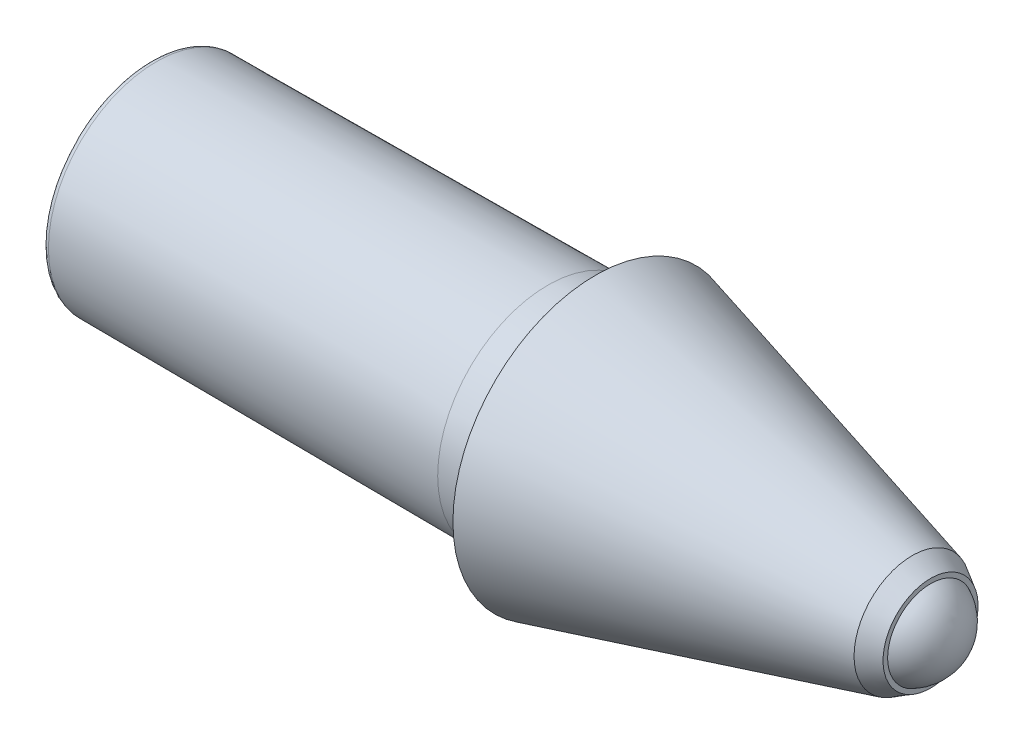
SolidWorks part; units mm, degrees
material "Latão"
ref_plane "Frontal" through (0, 0, 0) normal (0, 0, 1) x (1, 0, 0)
ref_plane "Superior" through (0, 0, 0) normal (0, 1, 0) x (1, 0, 0)
ref_plane "Lateral" through (0, 0, 0) normal (1, 0, 0) x (0, 0, -1)
sketch "Sketch1" plane through (0, 0, 0) normal (0, 0, 1) x (1, 0, 0)
  line L0 (-2, 0) -> (7.191, 0) construction
  line L1 (0, 0.465) -> (0, 0.8603)
  line L2 (0.0497, 0.9103) -> (3.35, 0.9285)
  line L3 (3.75, 1.15) -> (3.75, 1.2)
  line L4 (3, 0.45) -> (0.6362, 0.45)
  line L5 (3.35, 0.9285) -> (3.35, 0.9661) construction
  line L6 (3.75, 1.2) -> (6.4224, 0.4902)
  line L8 (6.5772, 0.4008) -> (6.4224, 0.4902)
  line L9 (3, 0.45) -> (3.0289, 0.4)
  line L10 (5.5866, 0.25) -> (6.0915, 0.25)
  line L11 (3.75, 1.15) -> (3.75, 0.93)
  line L12 (6.5772, 0.3621) -> (6.5772, 0.4008)
  line L13 (3.0289, 0.4) -> (5.5, 0.4)
  line L14 (5.5, 0.4) -> (5.5866, 0.25)
  line L15 (6.2415, 0.4) -> (6.0915, 0.25)
  line L16 (6.2415, 0.4) -> (6.4072, 0.4)
  line L17 (3.35, 0.9285) -> (3.75, 0.93)
  line L18 (0, 0.465) -> (0.6, 0.465)
  line L19 (0.6, 0.465) -> (0.6362, 0.45)
  line L20 (3.75, 1.15) -> (3.4241, 1.0627) construction
  arc A0 (0, 0.8603) -> (0.0497, 0.9103) centre (0.05, 0.8603) cw
  arc A2 (6.5772, 0.3621) -> (6.4072, 0.4) centre (6.4072, 0) ccw
  arc A3 (3.35, 0.9661) -> (3.4241, 1.0627) centre (3.45, 0.9661) cw construction
  circle A4 centre (6.4072, 0) radius 0.4 construction
  point P9 (0, 0.91)
  point P15 (6.8072, 0)
  point P24 (6.5772, 0.3814)
  point P30 (3.35, 1.0428)
  dimension "D3" = 2.4
  dimension "D11" = 0.4
  dimension "D21" = 14.875
  dimension "D16" = 30
  dimension "D5" = 6.5772
  dimension "D20" = 14.875
  dimension "D13" = 0.5
  dimension "D6" = 0.05
  dimension "D28" = 0.465
  dimension "D30" = 0.6
  dimension "D34" = 0.1
  dimension "D36" = 0.8
  dimension "D4" = 0.8016
  dimension "D7" = 2.3
  dimension "D8" = 0.9
  dimension "D9" = 2.4
  dimension "D10" = 1.82
  dimension "D12" = 0.23
  dimension "D14" = 60
  dimension "D18" = 0.8
  dimension "D19" = 5.5
  dimension "D22" = 2.8272
  dimension "D23" = 3.75
  dimension "D24" = 1.857
  dimension "D25" = 1.86
  dimension "D26" = 0.317
  dimension "D27" = 22.5
  dimension "D29" = 45
  dimension "D31" = 0.0894
  dimension "D32" = 2.0856
  dimension "D33" = 15
  dimension "D35" = 3
revolve "Base-Revolve" add sketch "Sketch1" angle 360 about L0
sketch "Sketch2" plane through (0, 0, 0) normal (0, 0, 1) x (1, 0, 0)
  line L0 (4.9797, 0) -> (7.1999, 0) construction
  line L1 (6.0072, 0) -> (6.8072, 0)
  line L2 (6.5772, -0.4491) -> (6.5772, 0.4491) construction
  arc A0 (6.8072, 0) -> (6.0072, 0) centre (6.4072, 0) ccw
  point P8 (6.5772, -0.3621)
  dimension "D2" = 0.4
  dimension "D1" = 0.23
  dimension "D3" = 0.7242
revolve "Esfera" add sketch "Sketch2" angle 360 about L0
